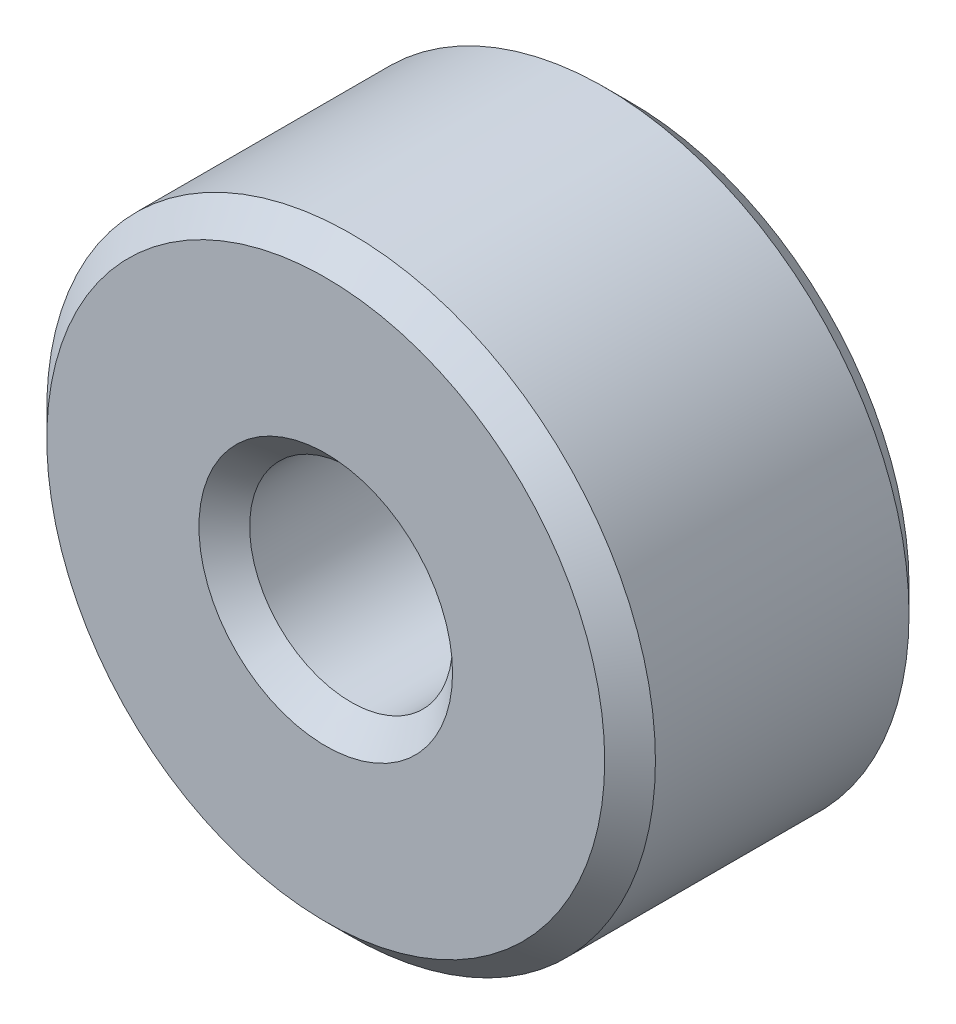
SolidWorks part; units mm, degrees
ref_plane "前视基准面" through (0, 0, 0) normal (0, 0, 1) x (1, 0, 0)
ref_plane "上视基准面" through (0, 0, 0) normal (0, 1, 0) x (1, 0, 0)
ref_plane "右视基准面" through (0, 0, 0) normal (1, 0, 0) x (0, 0, -1)
sketch "草图1" plane through (0, 0, 0) normal (0, 0, 1) x (1, 0, 0)
  circle A0 centre (0, 0) radius 1
  dimension "D1" = 2
extrude "拉伸-薄壁1" add sketch "草图1" along normal blind 3 thin
chamfer "倒角1" distance 0.25 angle 45 4 edges at (1, 0, 3) (3, 0, 3) (1, 0, 0) (3, 0, 0)
